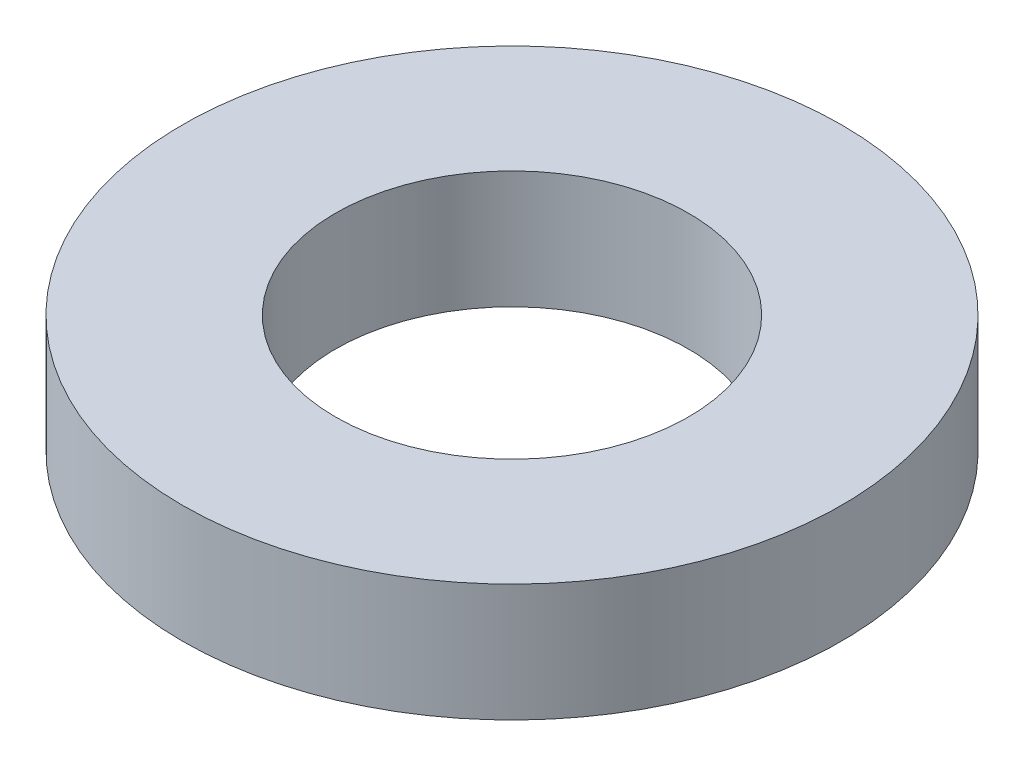
SolidWorks part; units mm, degrees
ref_plane "Front" through (0, 0, 0) normal (0, 0, 1) x (1, 0, 0)
ref_plane "Top" through (0, 0, 0) normal (0, 1, 0) x (1, 0, 0)
ref_plane "Right" through (0, 0, 0) normal (1, 0, 0) x (0, 0, -1)
sketch "Sketch1" plane through (0, 0, 0) normal (0, 1, 0) x (1, 0, 0)
  circle A0 centre (0, 0) radius 1.5
  circle A1 centre (0, 0) radius 2.8
extrude "Boss-Extrude1" add sketch "Sketch1" along normal blind 1
